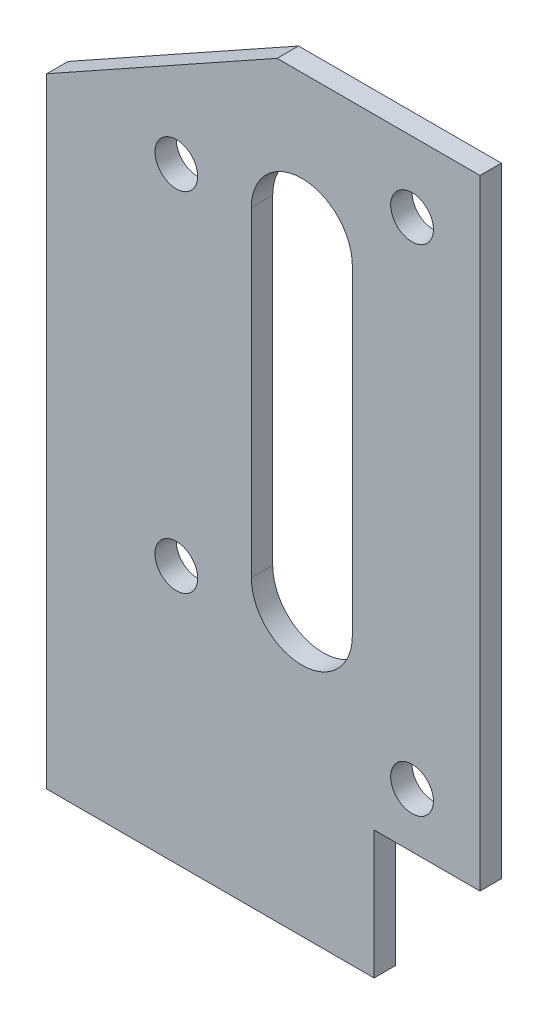
SolidWorks part; units mm, degrees
ref_plane "Front Plane" through (0, 0, 0) normal (0, 0, 1) x (1, 0, 0)
ref_plane "Top Plane" through (0, 0, 0) normal (0, 1, 0) x (1, 0, 0)
ref_plane "Right Plane" through (0, 0, 0) normal (1, 0, 0) x (0, 0, -1)
sketch "Sketch1" plane through (0, 0, 0) normal (0, 0, 1) x (1, 0, 0)
  line L7 (322.3825, -17.8593) -> (322.3825, 42.1407)
  line L8 (322.3825, 42.1407) -> (371.9449, 42.1407)
  line L9 (371.9449, 42.1407) -> (371.9449, 332.1407)
  line L10 (277.025, 332.1407) -> (169.1871, 271.9751)
  line L11 (169.1871, 271.9751) -> (169.1871, 205.17)
  line L16 (277.025, 332.1407) -> (371.9449, 332.1407)
  line L17 (169.1871, -17.8593) -> (322.3825, -17.8593)
  line L20 (288.5916, 265.6711) -> (288.5916, 115.6711) construction
  line L21 (312.226, 265.6711) -> (312.226, 115.6711)
  line L22 (264.9573, 265.6711) -> (264.9573, 115.6711)
  line L26 (169.1871, 205.17) -> (169.1871, -17.8593)
  arc A0 (312.226, 265.6711) -> (264.9573, 265.6711) centre (288.5916, 265.6711) ccw
  arc A1 (264.9573, 115.6711) -> (312.226, 115.6711) centre (288.5916, 115.6711) ccw
  circle A9 centre (229.8703, 265.6711) radius 10
  circle A10 centre (229.8703, 102.8253) radius 10
  circle A11 centre (340.1596, 299.3232) radius 10
  circle A12 centre (340.1596, 67.6675) radius 10
  point P19 (288.5916, 190.6711)
  dimension "D2" = 20
  dimension "D3" = 150
extrude "Boss-Extrude1" add sketch "Sketch1" along normal blind 10
